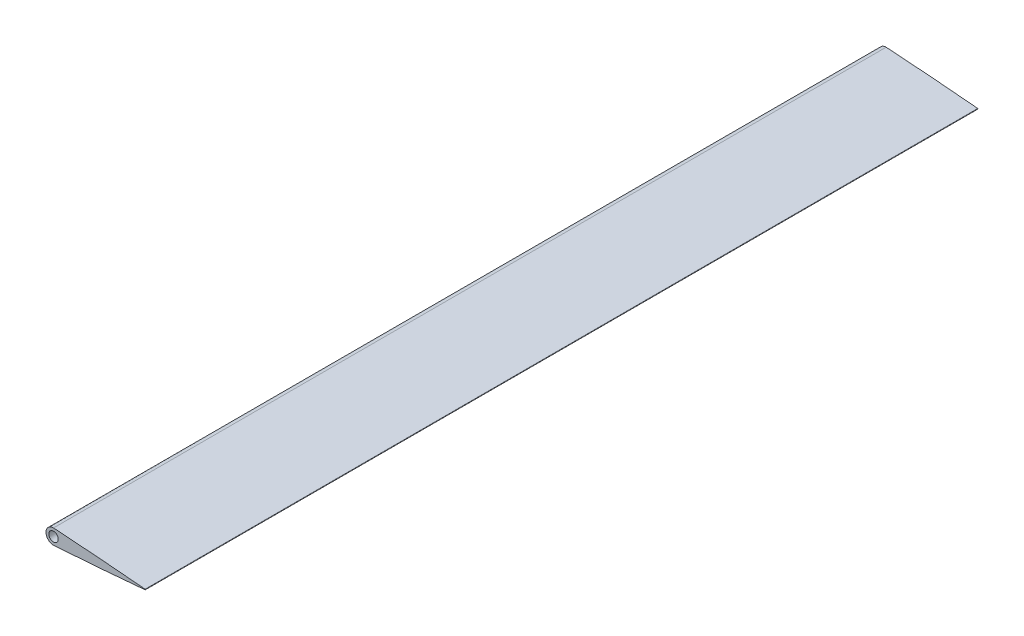
SolidWorks part; units mm, degrees
material "Foam"
ref_plane "Piano frontale" through (0, 0, 0) normal (0, 0, 1) x (1, 0, 0)
ref_plane "Piano superiore" through (0, 0, 0) normal (0, 1, 0) x (1, 0, 0)
ref_plane "Piano destro" through (0, 0, 0) normal (1, 0, 0) x (0, 0, -1)
curve "Curva1"
  spline degree 3 poles (100, 0.084, 0) (98.3335, 0.2367, 0) (95.0012, 0.5422, 0) (88.3356, 1.1109, 0) (80.0033, 1.7636, 0) (70.003, 2.4579, 0) (60.0031, 3.0617, 0) (50.003, 3.5521, 0) (40.0026, 3.9029, 0) (31.667, 4.0253, 0) (24.9992, 3.9769, 0) (19.9978, 3.845, 0) (14.9934, 3.5925, 0) (10.8272, 3.2377, 0) (7.4891, 2.814, 0) (4.9936, 2.4037, 0) (2.8496, 1.8679, 0) (1.1654, 1.321, 0) (-0.6646, 0, 0) (1.1654, -1.321, 0) (2.8496, -1.8679, 0) (4.9936, -2.4037, 0) (7.4891, -2.814, 0) (10.8272, -3.2377, 0) (14.9934, -3.5925, 0) (19.9978, -3.845, 0) (24.9992, -3.9769, 0) (31.667, -4.0253, 0) (40.0026, -3.9029, 0) (50.003, -3.5521, 0) (60.0031, -3.0617, 0) (70.003, -2.4579, 0) (80.0033, -1.7636, 0) (88.3356, -1.1109, 0) (95.0012, -0.5422, 0) (98.3335, -0.2367, 0) (100, -0.084, 0) knots 0 0 0 0 0.024876 0.049742 0.099443 0.149112 0.198751 0.248359 0.297937 0.347491 0.372267 0.397051 0.421859 0.446731 0.45922 0.471791 0.48456 0.491195 0.5 0.508805 0.51544 0.528209 0.54078 0.553269 0.578141 0.602949 0.627733 0.652509 0.702063 0.751641 0.801249 0.850888 0.900557 0.950258 0.975124 1 1 1 1
sketch "Schizzo1" plane through (0, 0, 0) normal (0, 0, 1) x (1, 0, 0)
  line L0 (71, 2.3776) -> (71, -2.3776) construction
  arc A0 (100, 0.084) -> (100, -0.084) centre (100, 0) cw
  arc A1 (71, 2.3776) -> (71, -2.3776) centre (71, 0) ccw
  spline S1 degree 3 poles (100, 0.084) (98.3335, 0.2367) (95.0012, 0.5422) (88.3356, 1.1109) (80.3363, 1.7375) (74.0008, 2.1802) (71, 2.3776) knots 0 0 0 0 0.024876 0.049742 0.099443 0.144147 0.144147 0.144147 0.144147
  spline S2 degree 3 poles (71, -2.3776) (74.0008, -2.1802) (80.3363, -1.7375) (88.3356, -1.1109) (95.0012, -0.5422) (98.3335, -0.2367) (100, -0.084) knots 0.855853 0.855853 0.855853 0.855853 0.900557 0.950258 0.975124 1 1 1 1
  spline S3 degree 3 poles (774.5938, 2905.893) (370.1816, -60.6448) (232.5901, -11.1972) (88.3356, 1.1109) (80.0033, 1.7636) (70.003, 2.4579) (60.0031, 3.0617) (50.003, 3.5521) (40.0026, 3.9029) (31.667, 4.0253) (24.9992, 3.9769) (19.9978, 3.845) (14.9934, 3.5925) (10.8272, 3.2377) (7.4891, 2.814) (4.9936, 2.4037) (2.8496, 1.8679) (1.1654, 1.321) (-0.6646, 0) (1.1654, -1.321) (2.8496, -1.8679) (4.9936, -2.4037) (7.4891, -2.814) (10.8272, -3.2377) (14.9934, -3.5925) (19.9978, -3.845) (24.9992, -3.9769) (31.667, -4.0253) (40.0026, -3.9029) (50.003, -3.5521) (60.0031, -3.0617) (70.003, -2.4579) (80.0033, -1.7636) (88.3356, -1.1109) (232.5893, 11.1971) (370.1799, 60.6442) (774.5865, -2905.8392) knots -2.052665 -2.052665 -2.052665 -2.052665 0.024876 0.049742 0.099443 0.149112 0.198751 0.248359 0.297937 0.347491 0.372267 0.397051 0.421859 0.446731 0.45922 0.471791 0.48456 0.491195 0.5 0.508805 0.51544 0.528209 0.54078 0.553269 0.578141 0.602949 0.627733 0.652509 0.702063 0.751641 0.801249 0.850888 0.900557 0.950258 0.975124 3.052652 3.052652 3.052652 3.052652 only from (100, 0.084) to (100, -0.084) construction
  spline S4 degree 3 poles (100, 0.084) (98.3335, 0.2367) (95.0012, 0.5422) (88.3356, 1.1109) (80.0033, 1.7636) (70.003, 2.4579) (60.0031, 3.0617) (50.003, 3.5521) (40.0026, 3.9029) (31.667, 4.0253) (24.9992, 3.9769) (19.9978, 3.845) (14.9934, 3.5925) (10.8272, 3.2377) (7.4891, 2.814) (4.9936, 2.4037) (2.8496, 1.8679) (1.1654, 1.321) (-0.6646, 0) (1.1654, -1.321) (2.8496, -1.8679) (4.9936, -2.4037) (7.4891, -2.814) (10.8272, -3.2377) (14.9934, -3.5925) (19.9978, -3.845) (24.9992, -3.9769) (31.667, -4.0253) (40.0026, -3.9029) (50.003, -3.5521) (60.0031, -3.0617) (70.003, -2.4579) (80.0033, -1.7636) (88.3356, -1.1109) (95.0012, -0.5422) (98.3335, -0.2367) (100, -0.084) knots 0 0 0 0 0.024876 0.049742 0.099443 0.149112 0.198751 0.248359 0.297937 0.347491 0.372267 0.397051 0.421859 0.446731 0.45922 0.471791 0.48456 0.491195 0.5 0.508805 0.51544 0.528209 0.54078 0.553269 0.578141 0.602949 0.627733 0.652509 0.702063 0.751641 0.801249 0.850888 0.900557 0.950258 0.975124 1 1 1 1 construction
  dimension "D3" = 0.084
  dimension "D1" = 29
  dimension "D2" = 4.7553
extrude "FoamEquilibratore" add sketch "Schizzo1" along normal blind 263.67
sketch "Schizzo2" plane through (0, 0, 263.67) normal (0, 0, 1) x (1, 0, 0)
  line L0 (71, 2.3776) -> (71, -2.3776) construction
  circle A0 centre (71, 0) radius 1.5
  dimension "D1" = 3
extrude "ForoPerno" cut sketch "Schizzo2" against normal through all
ref_plane "PianoMedio" through (0, 0, 140) normal (0, 0, 1) x (1, 0, 0)
